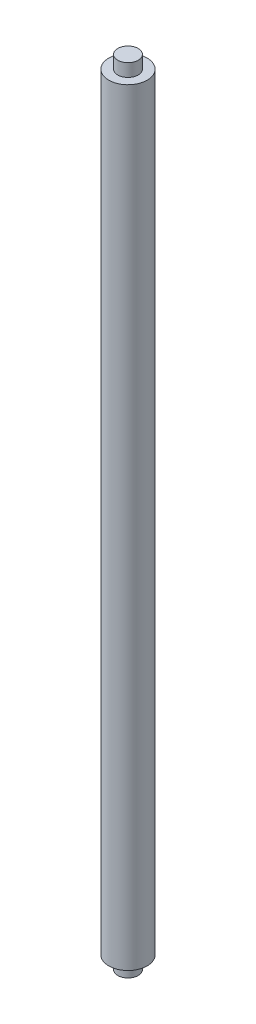
SolidWorks part; units mm, degrees
ref_plane "前视基准面" through (0, 0, 0) normal (0, 0, 1) x (1, 0, 0)
ref_plane "上视基准面" through (0, 0, 0) normal (0, 1, 0) x (1, 0, 0)
ref_plane "右视基准面" through (0, 0, 0) normal (1, 0, 0) x (0, 0, -1)
sketch "草图1" plane through (0, 0, 0) normal (0, 1, 0) x (1, 0, 0)
  circle A0 centre (0, 0) radius 0.8
  dimension "D1" = 1.6
extrude "凸台-拉伸1" add sketch "草图1" along normal mid plane 62
sketch "草图2" plane through (0, 0, 0) normal (0, 1, 0) x (1, 0, 0)
  circle A0 centre (0, 0) radius 1.5
  dimension "D1" = 3
extrude "凸台-拉伸2" add sketch "草图2" along normal mid plane 60
